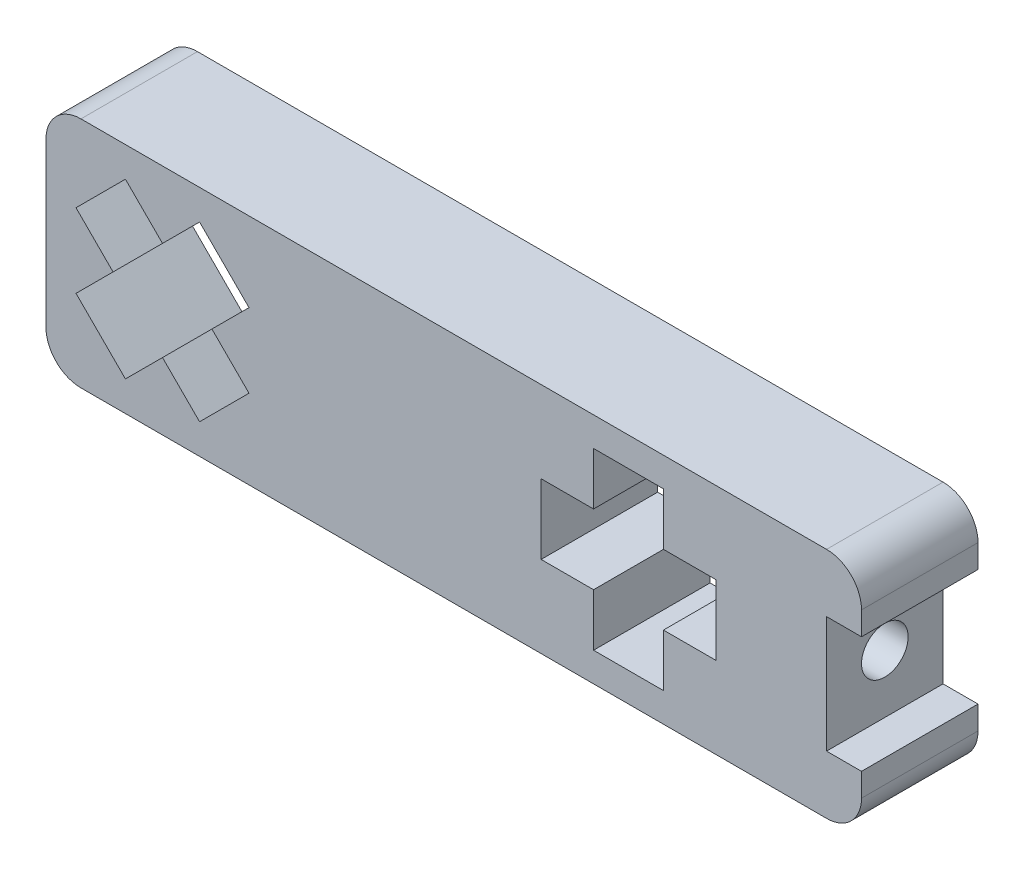
SolidWorks part; units mm, degrees
ref_plane "Front Plane" through (0, 0, 0) normal (0, 0, 1) x (1, 0, 0)
ref_plane "Top Plane" through (0, 0, 0) normal (0, 1, 0) x (1, 0, 0)
ref_plane "Right Plane" through (0, 0, 0) normal (1, 0, 0) x (0, 0, -1)
sketch "Sketch1" plane through (0, 0, 0) normal (0, 0, 1) x (1, 0, 0)
  line L0 (0, 0) -> (-20, 0) construction
  line L1 (30, 10) -> (-30, 10)
  line L2 (30, 10) -> (30, -10)
  line L3 (30, -10) -> (-30, -10)
  line L4 (-30, 10) -> (-30, -10)
  line L5 (30, 10) -> (-30, -10) construction
  line L6 (30, -10) -> (-30, 10) construction
  line L7 (-20, 0) -> (20, 0) construction
  line L9 (-23.182, 7.4246) -> (-27.4246, 3.182)
  line L10 (-23.182, 7.4246) -> (-20, 4.2426)
  line L11 (-12.5754, -3.182) -> (-16.818, -7.4246)
  line L12 (-27.4246, 3.182) -> (-24.2426, 0)
  line L13 (-23.182, 7.4246) -> (-16.818, -7.4246) construction
  line L14 (-12.5754, -3.182) -> (-27.4246, 3.182) construction
  line L15 (-16.818, 7.4246) -> (-20, 4.2426)
  line L16 (-16.818, 7.4246) -> (-12.5754, 3.182)
  line L17 (-12.5754, 3.182) -> (-15.7574, 0)
  line L18 (-27.4246, -3.182) -> (-23.182, -7.4246)
  line L19 (-16.818, 7.4246) -> (-23.182, -7.4246) construction
  line L20 (-12.5754, 3.182) -> (-27.4246, -3.182) construction
  line L21 (23, 7.5) -> (17, 7.5)
  line L22 (23, 7.5) -> (23, 3)
  line L23 (23, -7.5) -> (17, -7.5)
  line L24 (17, 7.5) -> (17, 3)
  line L25 (23, 7.5) -> (17, -7.5) construction
  line L26 (23, -7.5) -> (17, 7.5) construction
  line L27 (27.5, 3) -> (23, 3)
  line L28 (27.5, 3) -> (27.5, -3)
  line L29 (27.5, -3) -> (23, -3)
  line L30 (12.5, 3) -> (12.5, -3)
  line L31 (27.5, 3) -> (12.5, -3) construction
  line L32 (27.5, -3) -> (12.5, 3) construction
  line L33 (-20, -4.2426) -> (-23.182, -7.4246)
  line L34 (-15.7574, 0) -> (-12.5754, -3.182)
  line L35 (-20, -4.2426) -> (-16.818, -7.4246)
  line L36 (-24.2426, 0) -> (-27.4246, -3.182)
  line L37 (17, 3) -> (12.5, 3)
  line L38 (23, -3) -> (23, -7.5)
  line L39 (17, -3) -> (12.5, -3)
  line L40 (17, -3) -> (17, -7.5)
  point P0 (0, 0)
  point P25 (0, 0)
  dimension "D1" = 20
  dimension "D2" = 20
  dimension "D3" = 20
  dimension "D4" = 60
  dimension "D5" = 6
  dimension "D6" = 6
  dimension "D7" = 15
  dimension "D8" = 15
  dimension "D9" = 6
  dimension "D10" = 6
  dimension "D11" = 15
  dimension "D12" = 15
  dimension "D13" = 4.5
  dimension "D14" = 4.5
  dimension "D15" = 4.5
  dimension "D16" = 4.5
  dimension "D17" = 4.5
  dimension "D18" = 4.5
  dimension "D19" = 6
  dimension "D20" = 6
  dimension "D21" = 4.5
extrude "Boss-Extrude5" add sketch "Sketch1" along normal blind 10
sketch "Sketch4" plane through (30, 0, 0) normal (1, 0, 0) x (0, 0, -1)
  line L1 (0, -10) -> (-10, -10)
  line L2 (0, -10) -> (0, 10)
  line L3 (0, 10) -> (-10, 10)
  line L4 (-10, -10) -> (-10, 10)
extrude "Boss-Extrude6" add sketch "Sketch4" along normal blind 10
sketch "Sketch5" plane through (40, 0, 0) normal (1, 0, 0) x (0, 0, -1)
  line L0 (-10, -10) -> (0, 10) construction
  line L1 (-10, 10) -> (-10, -10) construction
  line L2 (0, -5) -> (-10, -5)
  line L3 (0, -5) -> (0, 5)
  line L4 (0, 5) -> (-10, 5)
  line L5 (-10, -5) -> (-10, 5)
  line L6 (0, -5) -> (-10, 5) construction
  line L7 (0, 5) -> (-10, -5) construction
  point P4 (-5, 0)
  dimension "D1" = 10
extrude "Cut-Extrude4" cut sketch "Sketch5" against normal blind 3
sketch "Sketch6" plane through (37, 0, 0) normal (1, 0, 0) x (0, 0, -1)
  line L0 (0, -5) -> (-10, 5) construction
  circle A0 centre (-5, 0) radius 2
extrude "Cut-Extrude5" cut sketch "Sketch6" against normal blind 14
fillet "Fillet2" radius 3 4 edges at (40, 10, 5) (40, -10, 5) (-30, 10, 5) (-30, -10, 5)
